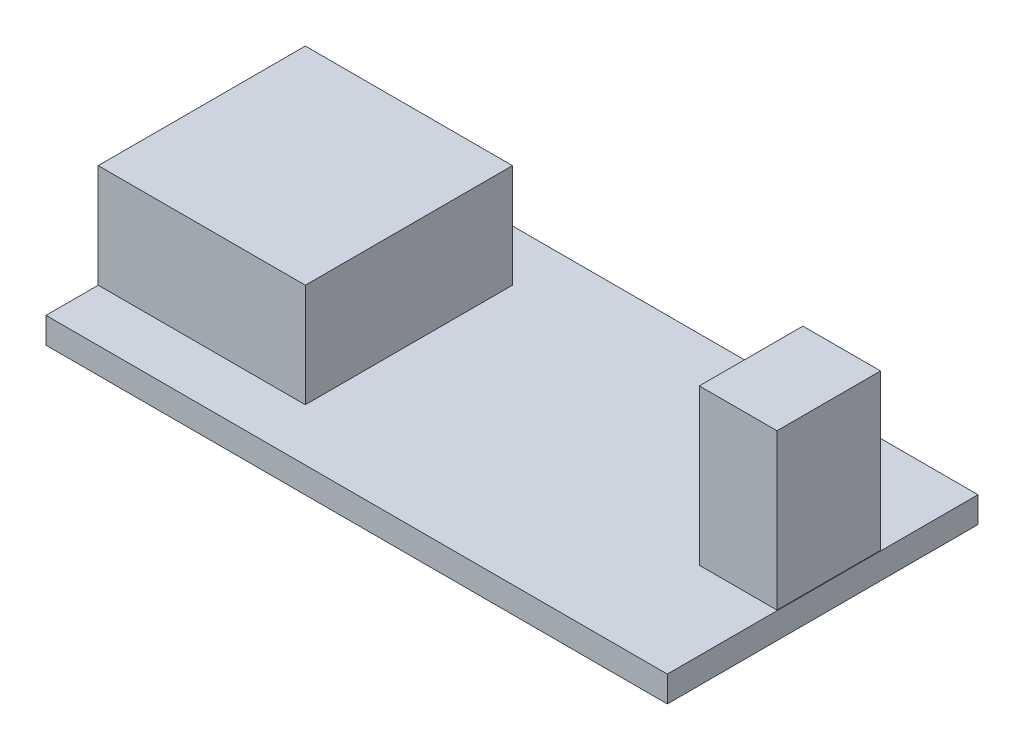
SolidWorks part; units mm, degrees
ref_plane "Front Plane" through (0, 0, 0) normal (0, 0, 1) x (1, 0, 0)
ref_plane "Top Plane" through (0, 0, 0) normal (0, 1, 0) x (1, 0, 0)
ref_plane "Right Plane" through (0, 0, 0) normal (1, 0, 0) x (0, 0, -1)
sketch "Sketch1" plane through (0, 0, 0) normal (0, 1, 0) x (1, 0, 0)
  line L1 (-152.4, -76.2) -> (152.4, -76.2)
  line L2 (-152.4, -76.2) -> (-152.4, 76.2)
  line L3 (-152.4, 76.2) -> (152.4, 76.2)
  line L4 (152.4, -76.2) -> (152.4, 76.2)
  line L5 (-152.4, -76.2) -> (152.4, 76.2) construction
  line L6 (-152.4, 76.2) -> (152.4, -76.2) construction
  point P0 (0, 0)
  dimension "D1" = 304.8
  dimension "D2" = 152.4
extrude "Boss-Extrude1" add sketch "Sketch1" along normal blind 12.7
sketch "Sketch2" plane through (0, 12.7, 0) normal (0, 1, 0) x (1, 0, 0)
  line L0 (152.4, -76.2) -> (152.4, 76.2) construction
  line L1 (114.0209, 28.6672) -> (152.1209, 28.6672)
  line L2 (114.0209, 28.6672) -> (114.0209, -22.1328)
  line L3 (114.0209, -22.1328) -> (152.1209, -22.1328)
  line L4 (152.1209, 28.6672) -> (152.1209, -22.1328)
  dimension "D1" = 38.1
  dimension "D2" = 50.8
  dimension "D3" = 0.2791
extrude "Boss-Extrude2" add sketch "Sketch2" along normal blind 76.2
sketch "Sketch3" plane through (0, 12.7, 0) normal (0, 1, 0) x (1, 0, 0)
  line L0 (-152.4, 76.2) -> (-152.4, -76.2) construction
  line L1 (-50.8, -50.5821) -> (-152.4, -50.5821)
  line L2 (-50.8, -50.5821) -> (-50.8, 51.0179)
  line L3 (-50.8, 51.0179) -> (-152.4, 51.0179)
  line L4 (-152.4, -50.5821) -> (-152.4, 51.0179)
  line L5 (-50.8, -50.5821) -> (-152.4, 51.0179) construction
  line L6 (-50.8, 51.0179) -> (-152.4, -50.5821) construction
  point P0 (-101.6, 0.2179)
  dimension "D1" = 101.6
  dimension "4" = 101.6
extrude "Boss-Extrude3" add sketch "Sketch3" along normal blind 50.8
